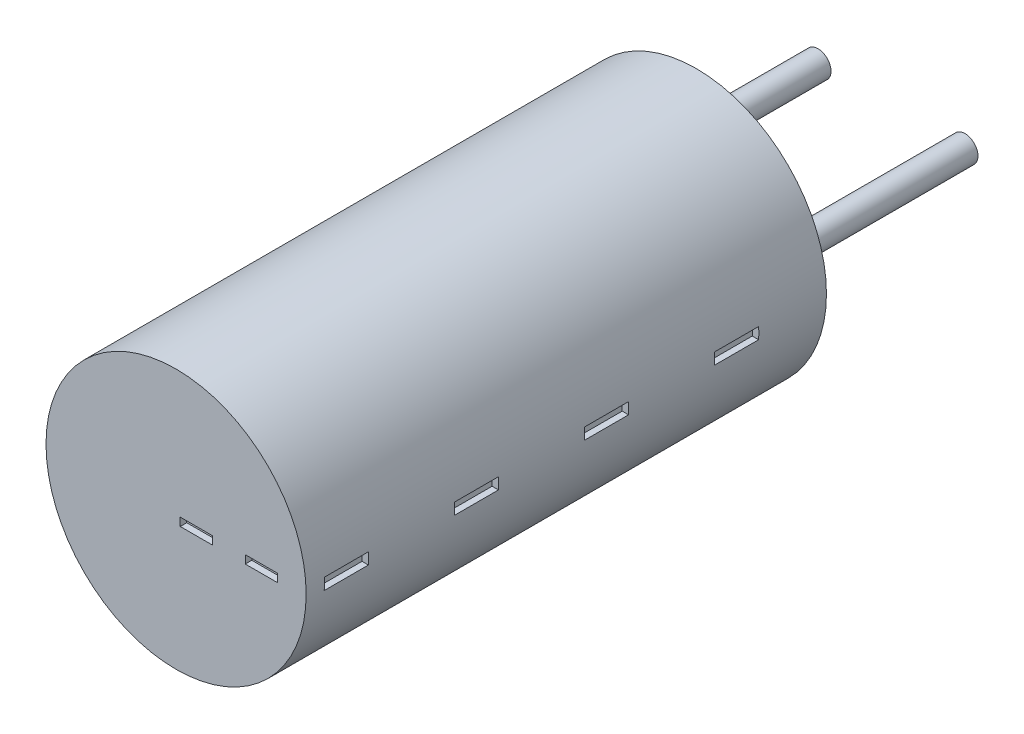
SolidWorks part; units mm, degrees
ref_plane "前视基准面" through (0, 0, 0) normal (0, 0, 1) x (1, 0, 0)
ref_plane "上视基准面" through (0, 0, 0) normal (0, 1, 0) x (1, 0, 0)
ref_plane "右视基准面" through (0, 0, 0) normal (1, 0, 0) x (0, 0, -1)
sketch "草图1" plane through (0, 0, 0) normal (0, 0, 1) x (1, 0, 0)
  line L0 (0, -1000) -> (0, 49000) construction
  line L1 (-1000, 0) -> (49000, 0) construction
  line L2 (0.75, 1.5694) -> (0.75, -2.1629) construction
  line L3 (-0.75, 1.5694) -> (-0.75, -2.1629) construction
  circle A0 centre (0, 0) radius 2
  dimension "D1" = 1.5
extrude "凸台-拉伸1" add sketch "草图1" along normal blind 8
sketch "草图2" plane through (0, 0, 0) normal (0, 0, -1) x (-1, 0, 0)
  line L0 (0, -1000) -> (0, 49000) construction
  line L1 (-1000, 0) -> (49000, 0) construction
  line L2 (1.13, 0.4256) -> (1.13, -0.529) construction
  line L3 (-1.13, 0.4256) -> (-1.13, -0.529) construction
  circle A0 centre (-1.13, 0) radius 0.2
  circle A1 centre (1.13, 0) radius 0.2
  dimension "D2" = 2.26
  dimension "D1" = 2.26
extrude "凸台-拉伸2" add sketch "草图2" along normal blind 3
ref_plane "基准面1" through (2, 0, 0) normal (1, 0, 0) x (0, 0, -1)
sketch "草图3" plane through (2, 0, 0) normal (1, 0, 0) x (0, 0, -1)
  line L0 (-8.0316, 0) -> (0, 0) construction
  line L1 (-5.7201, 0.0856) -> (-5.7201, -0.0909)
  line L2 (-7.7201, 0.0856) -> (-7.0407, 0.0856)
  line L3 (-7.7201, 0.0856) -> (-7.7201, -0.0909)
  line L4 (-7.7201, -0.0909) -> (-7.0407, -0.0909)
  line L5 (-7.0407, 0.0856) -> (-7.0407, -0.0909)
  line L6 (-5.7201, 0.0856) -> (-5.0407, 0.0856)
  line L7 (-5.0407, 0.0856) -> (-5.0407, -0.0909)
  line L8 (-5.7201, -0.0909) -> (-5.0407, -0.0909)
  line L9 (-3.7201, 0.0856) -> (-3.7201, -0.0909)
  line L10 (-3.7201, 0.0856) -> (-3.0407, 0.0856)
  line L11 (-3.0407, 0.0856) -> (-3.0407, -0.0909)
  line L12 (-3.7201, -0.0909) -> (-3.0407, -0.0909)
  line L13 (-1.7201, 0.0856) -> (-1.7201, -0.0909)
  line L14 (-1.7201, 0.0856) -> (-1.0407, 0.0856)
  line L15 (-1.0407, 0.0856) -> (-1.0407, -0.0909)
  line L16 (-1.7201, -0.0909) -> (-1.0407, -0.0909)
  dimension "D1" = 4
extrude "切除-拉伸1" cut sketch "草图3" against normal blind 0.1
sketch "草图6" plane through (0, 0, 8) normal (0, 0, 1) x (1, 0, 0)
  line L0 (0, 0) -> (2, 0) construction
  line L1 (2, -2.2) -> (2, 2.2) construction
  line L2 (1.064, 0.0599) -> (1.064, -0.0652)
  line L3 (0.064, 0.0599) -> (0.5593, 0.0599)
  line L4 (0.064, 0.0599) -> (0.064, -0.0652)
  line L5 (0.064, -0.0652) -> (0.5593, -0.0652)
  line L6 (0.5593, 0.0599) -> (0.5593, -0.0652)
  line L7 (1.064, 0.0599) -> (1.5593, 0.0599)
  line L8 (1.5593, 0.0599) -> (1.5593, -0.0652)
  line L9 (1.064, -0.0652) -> (1.5593, -0.0652)
  circle A0 centre (0, 0) radius 2 construction
  dimension "D1" = 2
extrude "切除-拉伸2" cut sketch "草图6" against normal blind 0.1
